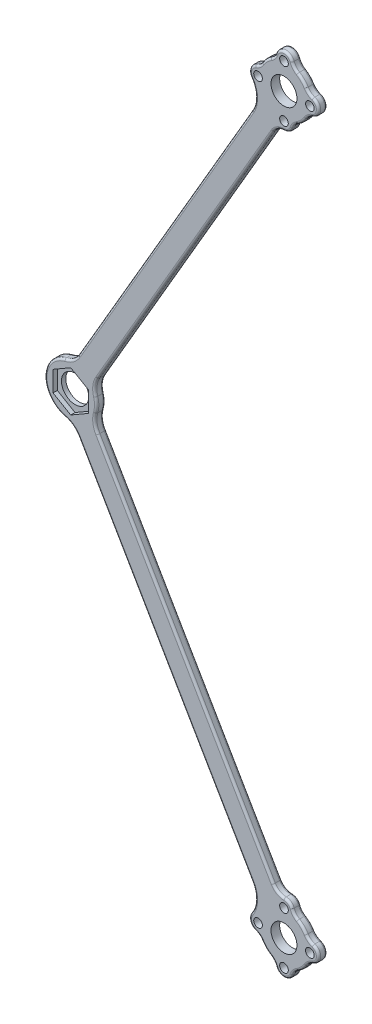
SolidWorks part; units mm, degrees
material "Hexcel AS4C (3000 丝)"
ref_plane "前视基准面" through (0, 0, 0) normal (0, 0, 1) x (1, 0, 0)
ref_plane "上视基准面" through (0, 0, 0) normal (0, 1, 0) x (1, 0, 0)
ref_plane "右视基准面" through (0, 0, 0) normal (1, 0, 0) x (0, 0, -1)
sketch "草图1" plane through (0, 0, 0) normal (0, 0, 1) x (1, 0, 0)
  line L0 (-92.2542, 77.298) -> (-132.4502, 8.1815)
  line L1 (-87.3648, 75.3617) -> (-127.9551, 5.5672)
  line L2 (-84.8528, 84.8528) -> (-134.2006, 0) construction
  line L3 (0, 0) -> (-134.2006, 0) construction
  line L4 (-92.2542, -77.298) -> (-132.4502, -8.1815)
  line L5 (-87.3648, -75.3617) -> (-127.9551, -5.5672)
  circle A0 centre (-134.2006, 0) radius 3.15 construction
  circle A1 centre (-84.8528, -90.8528) radius 1 construction
  circle A2 centre (-90.8528, -84.8528) radius 1 construction
  circle A3 centre (-84.8528, -78.8528) radius 1 construction
  circle A4 centre (-78.8528, -84.8528) radius 1 construction
  circle A5 centre (-84.8528, 78.8528) radius 1 construction
  circle A6 centre (-84.8528, 90.8528) radius 1 construction
  circle A7 centre (-78.8528, 84.8528) radius 1 construction
  circle A8 centre (-90.8528, 84.8528) radius 1 construction
  circle A9 centre (-134.2006, 0) radius 3.15
  circle A10 centre (-84.8528, -90.8528) radius 1
  circle A11 centre (-90.8528, -84.8528) radius 1
  circle A12 centre (-84.8528, -78.8528) radius 1
  circle A13 centre (-78.8528, -84.8528) radius 1
  circle A14 centre (-84.8528, 78.8528) radius 1
  circle A15 centre (-84.8528, 90.8528) radius 1
  circle A16 centre (-78.8528, 84.8528) radius 1
  circle A17 centre (-90.8528, 84.8528) radius 1
  arc A18 (-92.2542, 77.298) -> (-92.4998, 83.7182) centre (-97.4409, 80.3143) ccw
  arc A19 (-91.5195, 86.7384) -> (-92.4998, 83.7182) centre (-90.8528, 84.8528) ccw
  circle A23 centre (-84.8528, 84.8528) radius 6 construction
  circle A24 centre (-84.8528, 90.8528) radius 2 construction
  circle A28 centre (-84.8528, 84.8528) radius 3 construction
  circle A29 centre (-84.8528, 84.8528) radius 3
  circle A30 centre (-84.8528, -84.8528) radius 3 construction
  circle A31 centre (-84.8528, -84.8528) radius 3
  circle A32 centre (-78.8528, 84.8528) radius 2 construction
  circle A33 centre (-84.8528, 78.8528) radius 2 construction
  circle A34 centre (-90.8528, 84.8528) radius 2 construction
  arc A35 (-86.7384, 91.5195) -> (-82.9672, 91.5195) centre (-84.8528, 90.8528) cw
  arc A36 (-78.1861, 86.7384) -> (-78.1861, 82.9672) centre (-78.8528, 84.8528) cw
  arc A37 (-84.8203, 76.8531) -> (-82.9672, 78.1861) centre (-84.8528, 78.8528) ccw
  arc A38 (-91.5195, 86.7384) -> (-89.9639, 87.9955) centre (-92.5195, 89.5669) ccw
  arc A39 (-87.9955, 89.9639) -> (-89.9639, 87.9955) centre (-84.8528, 84.8528) ccw
  arc A40 (-81.7101, 89.9639) -> (-79.7417, 87.9955) centre (-84.8528, 84.8528) cw
  arc A41 (-79.7417, 81.7101) -> (-81.7101, 79.7417) centre (-84.8528, 84.8528) cw
  arc A42 (-82.9672, 91.5195) -> (-81.7101, 89.9639) centre (-80.1388, 92.5195) ccw
  arc A43 (-78.1861, 86.7384) -> (-79.7417, 87.9955) centre (-77.1861, 89.5669) cw
  arc A44 (-78.1861, 82.9672) -> (-79.7417, 81.7101) centre (-77.1861, 80.1388) ccw
  arc A45 (-87.3648, 75.3617) -> (-84.8203, 76.8531) centre (-84.7715, 73.8535) cw
  arc A46 (-82.9672, 78.1861) -> (-81.7101, 79.7417) centre (-80.1388, 77.1861) cw
  arc A47 (-86.7384, 91.5195) -> (-87.9955, 89.9639) centre (-89.5669, 92.5195) cw
  circle A48 centre (-134.2006, 0) radius 6 construction
  arc A49 (-135.6034, 5.8337) -> (-135.6034, -5.8337) centre (-134.2006, 0) ccw
  arc A50 (-128.4364, 1.6656) -> (-128.4364, -1.6656) centre (-134.2006, 0) cw
  arc A51 (-132.4502, 8.1815) -> (-135.6034, 5.8337) centre (-136.7724, 10.6951) cw
  arc A52 (-127.9551, 5.5672) -> (-128.4364, 1.6656) centre (-123.6329, 3.0536) ccw
  arc A53 (-132.4502, -8.1815) -> (-135.6034, -5.8337) centre (-136.7724, -10.6951) ccw
  arc A54 (-127.9551, -5.5672) -> (-128.4364, -1.6656) centre (-123.6329, -3.0536) cw
  arc A55 (-87.3648, -75.3617) -> (-84.8203, -76.8531) centre (-84.7715, -73.8535) ccw
  arc A56 (-84.8203, -76.8531) -> (-82.9672, -78.1861) centre (-84.8528, -78.8528) cw
  arc A57 (-82.9672, -78.1861) -> (-81.7101, -79.7417) centre (-80.1388, -77.1861) ccw
  arc A58 (-78.1861, -82.9672) -> (-79.7417, -81.7101) centre (-77.1861, -80.1388) cw
  arc A59 (-78.1861, -86.7384) -> (-78.1861, -82.9672) centre (-78.8528, -84.8528) ccw
  arc A60 (-78.1861, -86.7384) -> (-79.7417, -87.9955) centre (-77.1861, -89.5669) ccw
  arc A61 (-81.7101, -89.9639) -> (-79.7417, -87.9955) centre (-84.8528, -84.8528) ccw
  arc A62 (-82.9672, -91.5195) -> (-81.7101, -89.9639) centre (-80.1388, -92.5195) cw
  arc A63 (-86.7384, -91.5195) -> (-82.9672, -91.5195) centre (-84.8528, -90.8528) ccw
  arc A64 (-86.7384, -91.5195) -> (-87.9955, -89.9639) centre (-89.5669, -92.5195) ccw
  arc A65 (-87.9955, -89.9639) -> (-89.9639, -87.9955) centre (-84.8528, -84.8528) cw
  arc A66 (-91.5195, -86.7384) -> (-89.9639, -87.9955) centre (-92.5195, -89.5669) cw
  arc A67 (-91.5195, -86.7384) -> (-92.4998, -83.7182) centre (-90.8528, -84.8528) cw
  arc A68 (-92.2542, -77.298) -> (-92.4998, -83.7182) centre (-97.4409, -80.3143) cw
  arc A69 (-79.7417, -81.7101) -> (-81.7101, -79.7417) centre (-84.8528, -84.8528) ccw
  point P49 (-90.5195, 86.8248)
  point P62 (-82.8808, 90.5195)
  point P67 (-79.1861, 86.8248)
  point P70 (-79.1861, 82.8808)
  point P73 (-86.1962, 77.3712)
  point P76 (-82.8808, 79.1861)
  point P79 (-86.8248, 90.5195)
  point P87 (-133.7297, 5.9815)
  point P90 (-129.2346, 3.3673)
  dimension "D1" = 4
  dimension "D3" = 3
  dimension "D4" = 3
  dimension "D5" = 6
  dimension "D6" = 12
  dimension "D7" = 5
  dimension "D2" = 5.2
extrude "凸台-拉伸1" add sketch "草图1" along normal blind 2
fillet "圆角1" radius 0.5 80 edges at (-128.5953, 3.6657, 0) (-128.2006, 0, 0) (-128.5953, -3.6657, 0) (-107.66, -40.4645, 0) (-86.2885, -76.4417, 0) (-83.6849, -77.2293, 0) (-82.4721, -79.0718, 0) (-80.6102, -80.6102, 0) (-79.0718, -82.4721, 0) (-76.8528, -84.8528, 0) (-79.0718, -87.2335, 0) (-80.6102, -89.0955, 0) (-82.4721, -90.6339, 0) (-84.8528, -92.8528, 0) (-87.2335, -90.6339, 0) (-89.0955, -89.0955, 0) (-90.6339, -87.2335, 0) (-92.7551, -85.4703, 0) (-91.4452, -80.5437, 0) (-112.3522, -42.7397, 0) (-133.7864, -6.6847, 0) (-140.2006, 0, 0) (-133.7864, 6.6847, 0) (-112.3522, 42.7397, 0) (-91.4452, 80.5437, 0) (-92.7551, 85.4703, 0) (-90.6339, 87.2335, 0) (-89.0955, 89.0955, 0) (-87.2335, 90.6339, 0) (-84.8528, 92.8528, 0) (-82.4721, 90.6339, 0) (-80.6102, 89.0955, 0) (-79.0718, 87.2335, 0) (-76.8528, 84.8528, 0) (-79.0718, 82.4721, 0) (-80.6102, 80.6102, 0) (-82.4721, 79.0718, 0) (-83.6849, 77.2293, 0) (-86.2885, 76.4417, 0) (-128.5953, 3.6657, 2) (-128.2006, 0, 2) (-128.5953, -3.6657, 2) (-107.66, -40.4645, 2) (-86.2885, -76.4417, 2) (-83.6849, -77.2293, 2) (-82.4721, -79.0718, 2) (-80.6102, -80.6102, 2) (-79.0718, -82.4721, 2) (-76.8528, -84.8528, 2) (-79.0718, -87.2335, 2) (-80.6102, -89.0955, 2) (-82.4721, -90.6339, 2) (-84.8528, -92.8528, 2) (-87.2335, -90.6339, 2) (-89.0955, -89.0955, 2) (-90.6339, -87.2335, 2) (-92.7551, -85.4703, 2) (-91.4452, -80.5437, 2) (-112.3522, -42.7397, 2) (-133.7864, -6.6847, 2) (-140.2006, 0, 2) (-133.7864, 6.6847, 2) (-112.3522, 42.7397, 2) (-91.4452, 80.5437, 2) (-92.7551, 85.4703, 2) (-90.6339, 87.2335, 2) (-89.0955, 89.0955, 2) (-87.2335, 90.6339, 2) (-84.8528, 92.8528, 2) (-82.4721, 90.6339, 2) (-80.6102, 89.0955, 2) (-79.0718, 87.2335, 2) (-76.8528, 84.8528, 2) (-79.0718, 82.4721, 2) (-80.6102, 80.6102, 2) (-82.4721, 79.0718, 2) (-83.6849, 77.2293, 2) (-86.2885, 76.4417, 2) (-107.66, 40.4645, 0) (-107.66, 40.4645, 2)
sketch "草图2" plane through (0, 0, 2) normal (0, 0, 1) x (1, 0, 0)
  line L1 (-134.2006, 4.7343) -> (-138.3006, 2.3671)
  line L2 (-138.3006, 2.3671) -> (-138.3006, -2.3671)
  line L3 (-138.3006, -2.3671) -> (-134.2006, -4.7343)
  line L4 (-134.2006, -4.7343) -> (-130.1006, -2.3671)
  line L5 (-130.1006, -2.3671) -> (-130.1006, 2.3671)
  line L6 (-130.1006, 2.3671) -> (-134.2006, 4.7343)
  line L7 (-34.25, -0.6134) -> (-34.25, 0.6134) construction
  circle A0 centre (-134.2006, 0) radius 4.1 construction
  arc A2 (-135.4865, 5.3476) -> (-135.4865, -5.3476) centre (-134.2006, 0) ccw construction
  dimension "D1" = 8.2
extrude "切除-拉伸1" cut sketch "草图2" against normal blind 1
